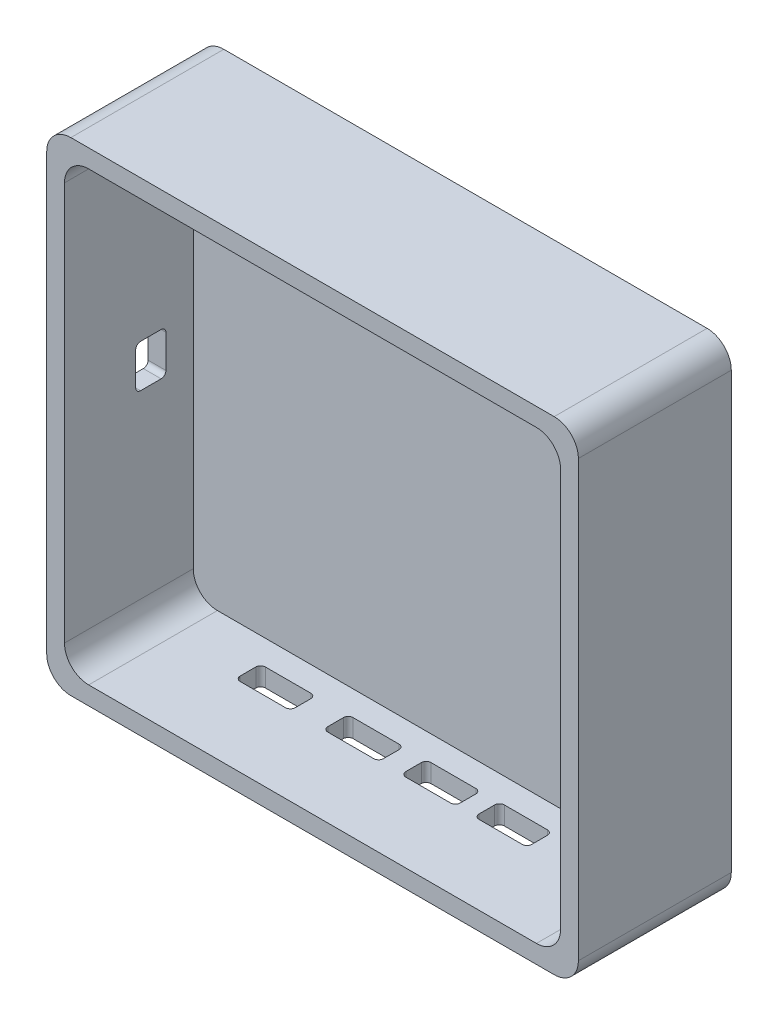
SolidWorks part; units mm, degrees
ref_plane "Plan de face" through (0, 0, 0) normal (0, 0, 1) x (1, 0, 0)
ref_plane "Plan de dessus" through (0, 0, 0) normal (0, 1, 0) x (1, 0, 0)
ref_plane "Plan de droite" through (0, 0, 0) normal (1, 0, 0) x (0, 0, -1)
sketch "Esquisse1" plane through (0, 0, 0) normal (0, 0, 1) x (1, 0, 0)
  line L1 (0, 0) -> (-110, 0)
  line L2 (0, 0) -> (0, 100)
  line L3 (0, 100) -> (-110, 100)
  line L4 (-110, 0) -> (-110, 100)
  dimension "D1" = 110
  dimension "D2" = 100
extrude "Boss.-Extru.1" add sketch "Esquisse1" along normal blind 60
fillet "Congé1" radius 5 4 edges at (0, 0, 30) (-110, 0, 30) (-110, 100, 30) (0, 100, 30)
sketch "Esquisse2" plane through (0, 0, 60) normal (0, 0, 1) x (1, 0, 0)
  line L1 (-3.6799, 96.2299) -> (-106.3201, 96.2299)
  line L2 (-3.6799, 96.2299) -> (-3.6799, 3.7701)
  line L3 (-3.6799, 3.7701) -> (-106.3201, 3.7701)
  line L4 (-106.3201, 96.2299) -> (-106.3201, 3.7701)
  line L5 (-3.6799, 96.2299) -> (-106.3201, 3.7701) construction
  line L6 (-3.6799, 3.7701) -> (-106.3201, 96.2299) construction
  point P0 (-55, 50)
extrude "Enlèv. mat.-Extru.1" cut sketch "Esquisse2" against normal blind 55
fillet "Congé2" radius 5 4 edges at (-3.6799, 3.7701, 32.5) (-106.3201, 3.7701, 32.5) (-3.6799, 96.2299, 32.5) (-106.3201, 96.2299, 32.5)
sketch "Esquisse3" plane through (0, 0, 0) normal (0, -1, 0) x (1, 0, 0)
  line L1 (-87.2424, 10.1448) -> (-75.8627, 10.1448)
  line L2 (-87.2424, 10.1448) -> (-87.2424, 15.3605)
  line L3 (-87.2424, 15.3605) -> (-75.8627, 15.3605)
  line L4 (-75.8627, 10.1448) -> (-75.8627, 15.3605)
  line L5 (-69.1061, 10.1448) -> (-57.6078, 10.1448)
  line L6 (-69.1061, 10.1448) -> (-69.1061, 15.3605)
  line L7 (-69.1061, 15.3605) -> (-57.6078, 15.3605)
  line L8 (-57.6078, 10.1448) -> (-57.6078, 15.3605)
  line L9 (-52.9848, 10.1448) -> (-41.7237, 10.1448)
  line L10 (-52.9848, 10.1448) -> (-52.9848, 15.3605)
  line L11 (-52.9848, 15.3605) -> (-41.7237, 15.3605)
  line L12 (-41.7237, 10.1448) -> (-41.7237, 15.3605)
  line L13 (-37.812, 10.1448) -> (-26.9064, 10.1448)
  line L14 (-37.812, 10.1448) -> (-37.812, 15.3605)
  line L15 (-37.812, 15.3605) -> (-26.9064, 15.3605)
  line L16 (-26.9064, 10.1448) -> (-26.9064, 15.3605)
extrude "Enlèv. mat.-Extru.2" cut sketch "Esquisse3" against normal blind 55
fillet "Congé3" radius 1 16 edges at (-26.9064, 1.885, 10.1448) (-26.9064, 1.885, 15.3605) (-37.812, 1.885, 15.3605) (-37.812, 1.885, 10.1448) (-52.9848, 1.885, 10.1448) (-41.7237, 1.885, 10.1448) (-41.7237, 1.885, 15.3605) (-52.9848, 1.885, 15.3605) (-57.6078, 1.885, 10.1448) (-57.6078, 1.885, 15.3605) (-69.1061, 1.885, 10.1448) (-69.1061, 1.885, 15.3605) (-75.8627, 1.885, 10.1448) (-75.8627, 1.885, 15.3605) (-87.2424, 1.885, 15.3605) (-87.2424, 1.885, 10.1448)
sketch "Esquisse4" plane through (-110, 0, 0) normal (-1, 0, 0) x (0, 0, 1)
  line L1 (10.6567, 54.9571) -> (16.9069, 54.9571)
  line L2 (10.6567, 54.9571) -> (10.6567, 46.1206)
  line L3 (10.6567, 46.1206) -> (16.9069, 46.1206)
  line L4 (16.9069, 54.9571) -> (16.9069, 46.1206)
extrude "Enlèv. mat.-Extru.3" cut sketch "Esquisse4" against normal blind 55 contours L2 L1 L4 L3
fillet "Congé4" radius 1 4 edges at (-108.1601, 46.1206, 16.9069) (-108.1601, 46.1206, 10.6567) (-108.1601, 54.9571, 10.6567) (-108.1601, 54.9571, 16.9069)
sketch "Esquisse6" plane through (0, 0, 0) normal (0, 1, 0) x (1, 0, 0)
  line L1 (-119.9899, -31.6404) -> (9.0983, -31.6404)
  line L2 (-119.9899, -31.6404) -> (-119.9899, -67.676)
  line L3 (-119.9899, -67.676) -> (9.0983, -67.676)
  line L4 (9.0983, -31.6404) -> (9.0983, -67.676)
extrude "Enlèv. mat.-Extru.5" cut sketch "Esquisse6" along normal blind 115 contours L2 L1 L4 L3
